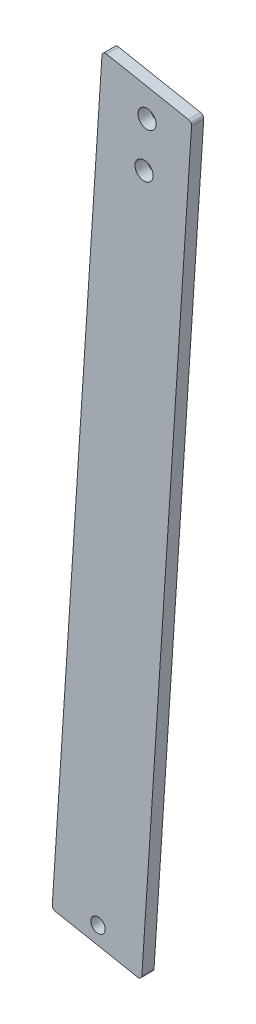
SolidWorks part; units mm, degrees
material "Thornel Mat VMA"
ref_plane "Alzado" through (0, 0, 0) normal (0, 0, 1) x (1, 0, 0)
ref_plane "Planta" through (0, 0, 0) normal (0, 1, 0) x (1, 0, 0)
ref_plane "Vista lateral" through (0, 0, 0) normal (1, 0, 0) x (0, 0, -1)
sketch "Croquis3" plane through (0, 0, 0) normal (0, 0, 1) x (1, 0, 0)
  line L0 (-26.1729, 20.4953) -> (-13.9636, 84.1124) construction
  line L3 (-1.7613, -84.6433) -> (-1.6114, -82.3482) construction
  line L9 (4.1312, -85.7742) -> (10.7356, 15.3258)
  line L10 (4.1312, -85.7742) -> (-7.6538, -83.5124)
  line L11 (10.7356, 15.3258) -> (-1.0494, 17.5876)
  line L12 (-7.6538, -83.5124) -> (-1.0494, 17.5876)
  circle A0 centre (4.8431, 12.7567) radius 1.2
  circle A1 centre (4.4506, 6.6776) radius 1.2
  circle A2 centre (-1.6114, -82.3482) radius 0.95
  point P2 (0, 0)
  point P3 (0, 0)
  point P5 (0, 0)
  point P6 (0, 0)
  point P7 (-1.0494, -32.4124)
  point P8 (0, 0)
  point P10 (0, 0)
  point P20 (0, 0)
  dimension "D2" = 2.4
  dimension "D5" = 2.4
  dimension "D3" = 12
  dimension "D7" = 1.9
  dimension "D4" = 101.1
  dimension "D6" = 2.3
extrude "Saliente-Extruir4" add sketch "Croquis3" along normal blind 1.6 contours A1 | A0 | L10 L12 L11 L9 | A2
fillet "Redondeo4" radius 0.5 1 edges at (10.7356, 15.3258, 0.8)
fillet "Redondeo5" radius 0.5 3 edges at (4.1312, -85.7742, 0.8) (-7.6538, -83.5124, 0.8) (-1.0494, 17.5876, 0.8)
